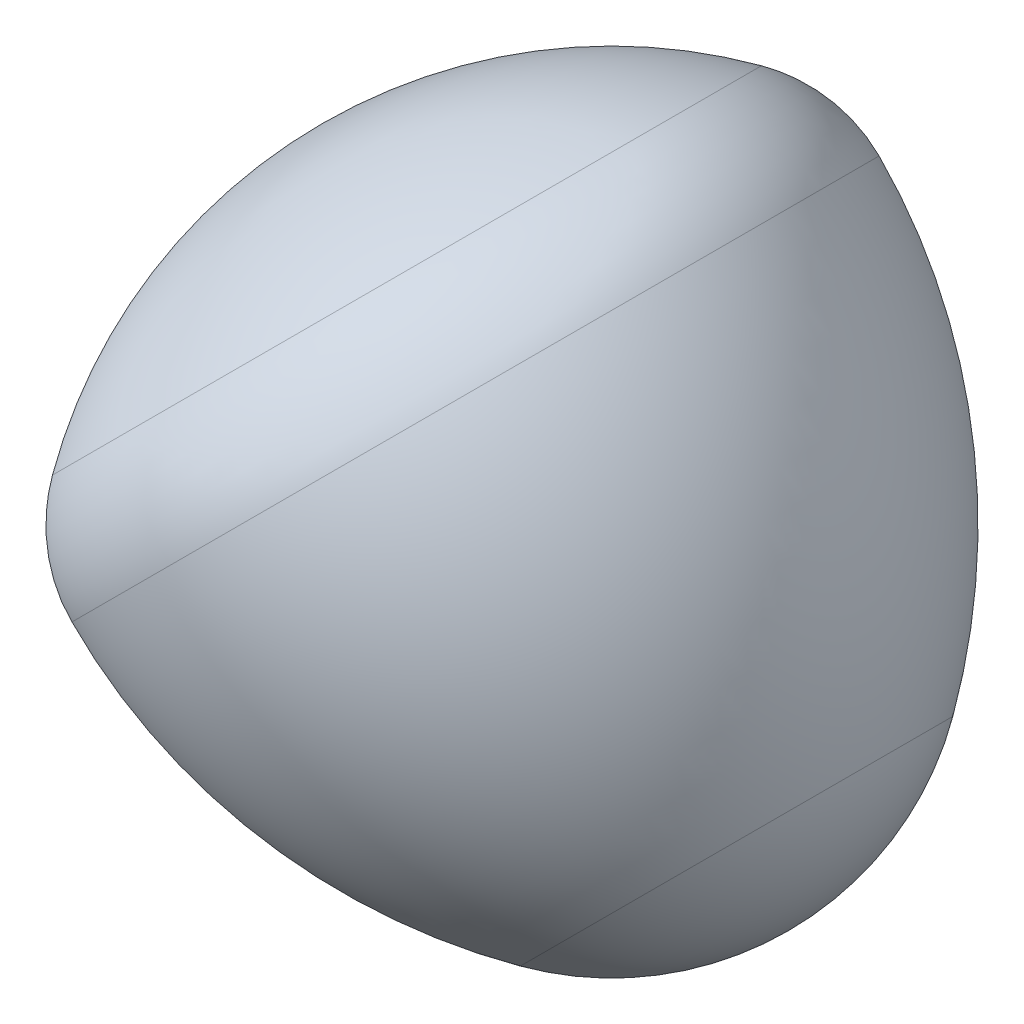
SolidWorks part; units mm, degrees
ref_plane "Front Plane" through (0, 0, 0) normal (0, 0, 1) x (1, 0, 0)
ref_plane "Top Plane" through (0, 0, 0) normal (0, 1, 0) x (1, 0, 0)
ref_plane "Right Plane" through (0, 0, 0) normal (1, 0, 0) x (0, 0, -1)
sketch "Sketch1" plane through (0, 0, 0) normal (0, 0, 1) x (1, 0, 0)
  line L0 (0, -4.0682) -> (0, 8.2176) construction
  line L1 (-5.1194, 15.5442) -> (-18.9489, 1.7147) construction
  line L2 (-14.3845, 0) -> (1.8574, 0) construction
  line L3 (-28.5967, 15.3178) -> (-12.4729, 31.4415) construction
  line L4 (-52.2865, 52.2865) -> (38.9813, -38.9813) construction
  line L5 (-6.4709, -33.267) -> (12.7081, -14.0881) construction
  line L6 (-21.9572, 21.9572) -> (13.3981, -13.3981)
  arc A1 (-21.9572, 21.9572) -> (0, 31.0522) centre (0, 0) cw
  arc A2 (0, 31.0522) -> (7.3459, 28.0095) centre (0, 20.6636) cw
  arc A3 (7.3459, 28.0095) -> (18.9478, 0) centre (-20.6636, 0) cw
  arc A4 (18.9478, 0) -> (13.3981, -13.3981) centre (0, 0) cw
  point P1 (0, 20.6636)
  point P8 (-20.6636, 0)
  dimension "D1" = 45
  dimension "D2" = 45
  dimension "D3" = 50
revolve "Revolve1" add sketch "Sketch1" angle 360 about L4
scale "Scale1" scale about centroid uniform scaling yes scale factor 0.5
